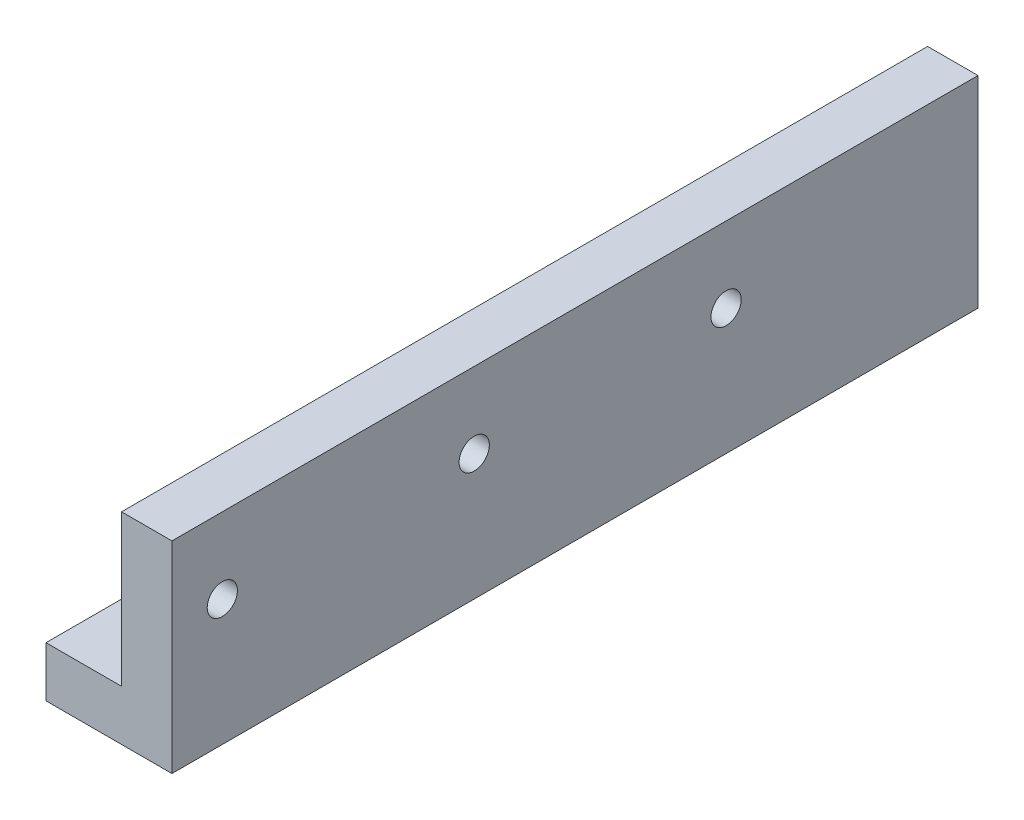
SolidWorks part; units mm, degrees
ref_plane "前基準面" through (0, 0, 0) normal (0, 0, 1) x (1, 0, 0)
ref_plane "上基準面" through (0, 0, 0) normal (0, 1, 0) x (1, 0, 0)
ref_plane "右基準面" through (0, 0, 0) normal (1, 0, 0) x (0, 0, -1)
sketch "草圖1" plane through (0, 0, 0) normal (0, 0, 1) x (1, 0, 0)
  line L0 (-5.3385, 191.7716) -> (-5.3385, 161.7716)
  line L2 (-5.3385, 161.7716) -> (-20.3385, 161.7716)
  line L3 (-20.3385, 161.7716) -> (-20.3385, 151.7716)
  line L4 (-20.3385, 151.7716) -> (4.6615, 151.7716)
  line L5 (4.6615, 151.7716) -> (4.6615, 191.7716)
  line L6 (4.6615, 191.7716) -> (-5.3385, 191.7716)
  dimension "D1" = 15
  dimension "D2" = 10
  dimension "D3" = 30
  dimension "D4" = 10
extrude "填料-伸長1" add sketch "草圖1" against normal blind 160
sketch "草圖2" plane through (4.6615, 0, 0) normal (1, 0, 0) x (0, 0, -1)
  line L1 (160, 161.7716) -> (0, 161.7716) construction
  line L3 (160, 151.7716) -> (160, 191.7716) construction
  circle A2 centre (110, 176.7716) radius 3
  dimension "D1" = 15
  dimension "D3" = 6
  dimension "D7" = 50
extrude "除料-伸長1" cut sketch "草圖2" against normal up to surface (10 mm away) and the other way through all up to face at (-5.3385, 176.7716, -80)
pattern_linear "LPattern1" count 3 spacing 50 along (0, 0, 1) of "除料-伸長1"
